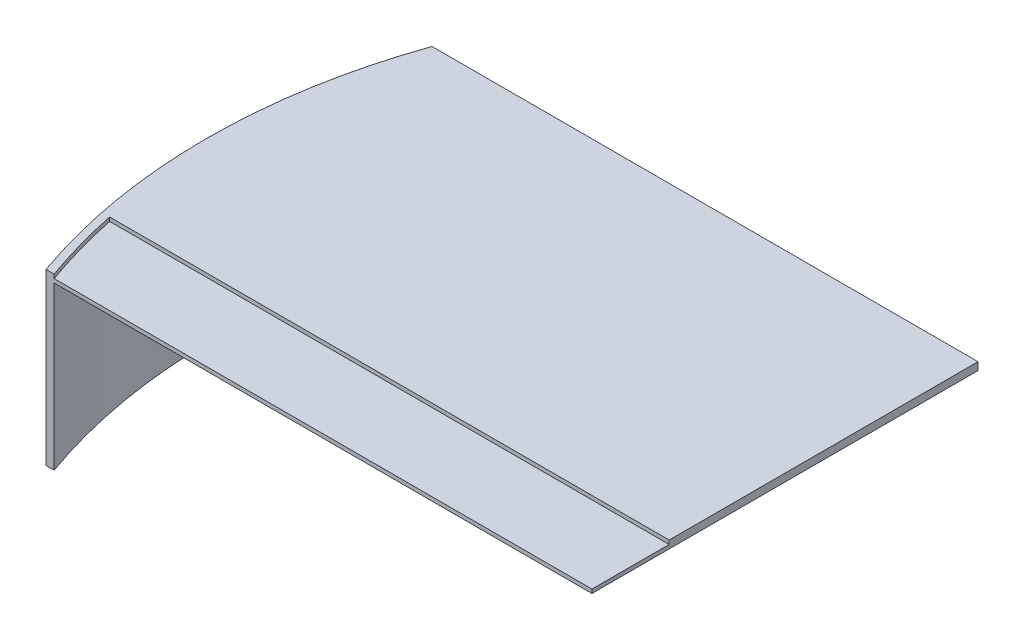
SolidWorks part; units mm, degrees
ref_plane "Front Plane" through (0, 0, 0) normal (0, 0, 1) x (1, 0, 0)
ref_plane "Top Plane" through (0, 0, 0) normal (0, 1, 0) x (1, 0, 0)
ref_plane "Right Plane" through (0, 0, 0) normal (1, 0, 0) x (0, 0, -1)
sketch "Sketch1" plane through (0, 0, 0) normal (0, 1, 0) x (1, 0, 0)
  line L0 (0, 0) -> (0, -50)
  line L2 (0, 0) -> (0, 50)
  line L3 (0, 50) -> (-141.4214, 50)
  line L4 (0, -50) -> (-141.4214, -50)
  arc A0 (-141.4214, 50) -> (-141.4214, -50) centre (0, 0) ccw
  point P3 (0, 50)
  point P6 (0, -50)
  dimension "D1" = 300
  dimension "D3" = 100
extrude "Boss-Extrude1" add sketch "Sketch1" along normal blind 44
shell "Shell1" thickness 2
sketch "Sketch2" plane through (0, 44, 0) normal (0, 1, 0) x (-1, 0, 0)
  line L0 (139.2982, 50) -> (0, 50)
  line L1 (0, 50) -> (0, 30)
  line L2 (0, 50) -> (0, -50) construction
  line L3 (0, 30) -> (144.9276, 30)
  arc A0 (139.2982, -50) -> (139.2982, 50) centre (0, 0) ccw construction
  arc A1 (144.9276, 30) -> (139.2982, 50) centre (0, 0) ccw
  line M1 (0, 50) -> (0, -50)
  line M4 (141.4214, 50) -> (0, 50)
  dimension "D1" = 20
extrude "Cut-Extrude1" cut sketch "Sketch2" against normal blind 1 contours L3 A1 M4 M1
